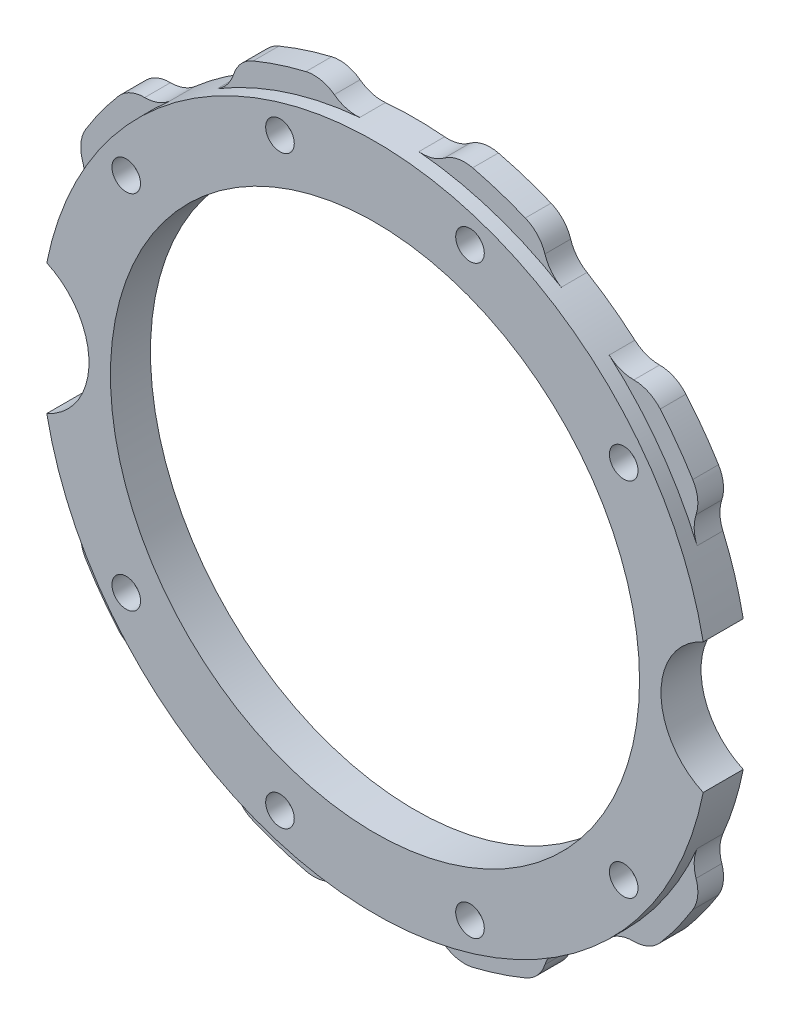
SolidWorks part; units mm, degrees
material "2014 Legierung"
ref_plane "Vorne" through (0, 0, 0) normal (0, 0, 1) x (1, 0, 0)
ref_plane "Oben" through (0, 0, 0) normal (0, 1, 0) x (1, 0, 0)
ref_plane "Rechts" through (0, 0, 0) normal (1, 0, 0) x (0, 0, -1)
sketch "Skizze1" plane through (0, 0, 0) normal (0, 0, 1) x (1, 0, 0)
  line L0 (3.9109, 24.6922) -> (3.6762, 23.2107) construction
  line L1 (0, 0) -> (0, 46.5) construction
  line L2 (-7.2742, 45.9275) -> (0, 0) construction
  line L3 (0, 0) -> (-10.9794, 21.5483) construction
  line L4 (-6.6439, 20.4477) -> (0, 0) construction
  arc A0 (15.4399, 17.7161) -> (17.1008, 17.1008) centre (17.0825, 19.6007) ccw construction
  arc A1 (17.1008, 17.1008) -> (19.0213, 16.2232) centre (17.1191, 14.6009) cw construction
  circle A2 centre (2.299, 25.8982) radius 2.5 construction
  circle A3 centre (5.2675, 21.8747) radius 2.5 construction
  arc A4 (2.0779, 23.408) -> (3.7832, 23.8864) centre (2.299, 25.8982) ccw construction
  arc A5 (3.7832, 23.8864) -> (5.8528, 24.3052) centre (5.2675, 21.8747) cw construction
  arc A6 (-2.0779, 23.408) -> (-3.7832, 23.8864) centre (-2.299, 25.8982) cw construction
  arc A7 (-3.7832, 23.8864) -> (-5.8528, 24.3052) centre (-5.2675, 21.8747) ccw construction
  arc A8 (12.0778, 20.1588) -> (10.9794, 21.5483) centre (13.3626, 22.3034) cw construction
  arc A9 (10.9794, 21.5483) -> (9.5513, 23.1035) centre (8.5962, 20.7932) ccw construction
  arc A10 (15.4399, 17.7161) -> (12.0778, 20.1588) centre (0, 0) ccw construction
  arc A11 (-22.9044, 5.2572) -> (-22.9044, -5.2572) centre (0, 0) ccw construction
  arc A12 (22.9044, 5.2572) -> (22.9044, -5.2572) centre (0, 0) cw construction
  arc A13 (21.6202, 9.2097) -> (21.5483, 10.9794) centre (23.9202, 10.1894) cw construction
  arc A14 (21.5483, 10.9794) -> (21.3071, 13.077) centre (19.1764, 11.7693) ccw construction
  arc A15 (22.9044, 5.2572) -> (21.6202, 9.2097) centre (0, 0) ccw construction
  arc A16 (21.6202, -9.2097) -> (21.5483, -10.9794) centre (23.9202, -10.1894) ccw construction
  arc A17 (21.5483, -10.9794) -> (21.3071, -13.077) centre (19.1764, -11.7693) cw construction
  arc A18 (-22.8069, 5.2348) -> (-22.8069, -5.2348) centre (0, 0) ccw
  arc A19 (-22.8069, -5.2348) -> (-21.5282, -9.1705) centre (0, 0) ccw
  arc A20 (21.6202, -9.2097) -> (22.9044, -5.2572) centre (0, 0) ccw construction
  arc A21 (12.0778, -20.1588) -> (10.9794, -21.5483) centre (13.3626, -22.3034) ccw construction
  arc A22 (10.9794, -21.5483) -> (9.5513, -23.1035) centre (8.5962, -20.7932) cw construction
  arc A23 (15.4399, -17.7161) -> (17.1008, -17.1008) centre (17.0825, -19.6007) cw construction
  arc A24 (17.1008, -17.1008) -> (19.0213, -16.2232) centre (17.1191, -14.6009) ccw construction
  arc A25 (12.0778, -20.1588) -> (15.4399, -17.7161) centre (0, 0) ccw construction
  arc A26 (-2.0779, -23.408) -> (-3.7832, -23.8864) centre (-2.299, -25.8982) ccw construction
  arc A27 (-3.7832, -23.8864) -> (-5.8528, -24.3052) centre (-5.2675, -21.8747) cw construction
  arc A28 (2.0779, -23.408) -> (3.7832, -23.8864) centre (2.299, -25.8982) cw construction
  arc A29 (3.7832, -23.8864) -> (5.8528, -24.3052) centre (5.2675, -21.8747) ccw construction
  arc A30 (-2.0779, -23.408) -> (2.0779, -23.408) centre (0, 0) ccw construction
  arc A31 (-15.4399, -17.7161) -> (-17.1008, -17.1008) centre (-17.0825, -19.6007) ccw construction
  arc A32 (-17.1008, -17.1008) -> (-19.0213, -16.2232) centre (-17.1191, -14.6009) cw construction
  arc A33 (-12.0778, -20.1588) -> (-10.9794, -21.5483) centre (-13.3626, -22.3034) cw construction
  arc A34 (-10.9794, -21.5483) -> (-9.5513, -23.1035) centre (-8.5962, -20.7932) ccw construction
  arc A35 (-15.4399, -17.7161) -> (-12.0778, -20.1588) centre (0, 0) ccw construction
  arc A36 (-21.5282, -9.1705) -> (-21.4534, -11.011) centre (-23.9202, -10.1894) cw
  arc A37 (-21.4534, -11.011) -> (-21.2218, -13.0247) centre (-19.1764, -11.7693) ccw
  arc A38 (-21.6202, -9.2097) -> (-21.5483, -10.9794) centre (-23.9202, -10.1894) cw construction
  arc A39 (-21.5483, -10.9794) -> (-21.3071, -13.077) centre (-19.1764, -11.7693) ccw construction
  arc A40 (-22.9044, -5.2572) -> (-21.6202, -9.2097) centre (0, 0) ccw construction
  arc A41 (-21.6202, 9.2097) -> (-21.5483, 10.9794) centre (-23.9202, 10.1894) ccw construction
  arc A42 (-21.5483, 10.9794) -> (-21.3071, 13.077) centre (-19.1764, 11.7693) cw construction
  arc A43 (-21.2218, -13.0247) -> (-18.9452, -16.1583) centre (0, 0) ccw
  arc A44 (-17.1015, -17.0008) -> (-18.9452, -16.1583) centre (-17.1191, -14.6009) cw
  arc A45 (-21.6202, 9.2097) -> (-22.9044, 5.2572) centre (0, 0) ccw construction
  arc A46 (-12.0778, 20.1588) -> (-10.9794, 21.5483) centre (-13.3626, 22.3034) ccw construction
  arc A47 (-10.9794, 21.5483) -> (-9.5513, 23.1035) centre (-8.5962, 20.7932) cw construction
  arc A48 (-15.4399, 17.7161) -> (-17.1008, 17.1008) centre (-17.0825, 19.6007) cw construction
  arc A49 (-17.1008, 17.1008) -> (-19.0213, 16.2232) centre (-17.1191, 14.6009) ccw construction
  arc A50 (-12.0778, 20.1588) -> (-15.4399, 17.7161) centre (0, 0) ccw construction
  arc A51 (-19.0213, 16.2232) -> (-21.3071, 13.077) centre (0, 0) ccw construction
  arc A52 (-5.8528, 24.3052) -> (-9.5513, 23.1035) centre (0, 0) ccw construction
  arc A53 (-15.3742, -17.6407) -> (-17.1015, -17.0008) centre (-17.0825, -19.6007) ccw
  arc A54 (9.5513, 23.1035) -> (5.8528, 24.3052) centre (0, 0) ccw construction
  arc A55 (21.3071, 13.077) -> (19.0213, 16.2232) centre (0, 0) ccw construction
  arc A56 (-21.3071, -13.077) -> (-19.0213, -16.2232) centre (0, 0) ccw construction
  arc A57 (-9.5513, -23.1035) -> (-5.8528, -24.3052) centre (0, 0) ccw construction
  arc A58 (5.8528, -24.3052) -> (9.5513, -23.1035) centre (0, 0) ccw construction
  arc A59 (19.0213, -16.2232) -> (21.3071, -13.077) centre (0, 0) ccw construction
  arc A60 (-15.3742, -17.6407) -> (-12.0264, -20.073) centre (0, 0) ccw
  arc A61 (-12.0264, -20.073) -> (-10.8841, -21.5181) centre (-13.3626, -22.3034) cw
  arc A62 (-10.8841, -21.5181) -> (-9.5131, -23.0111) centre (-8.5962, -20.7932) ccw
  arc A63 (-9.5131, -23.0111) -> (-5.8294, -24.208) centre (0, 0) ccw
  arc A64 (-3.8426, -23.806) -> (-5.8294, -24.208) centre (-5.2675, -21.8747) cw
  arc A65 (-2.0691, -23.3083) -> (-3.8426, -23.806) centre (-2.299, -25.8982) ccw
  arc A66 (-2.0691, -23.3083) -> (2.0691, -23.3083) centre (0, 0) ccw
  arc A67 (2.0691, -23.3083) -> (3.8426, -23.806) centre (2.299, -25.8982) cw
  arc A68 (3.8426, -23.806) -> (5.8294, -24.208) centre (5.2675, -21.8747) ccw
  arc A69 (5.8294, -24.208) -> (9.5131, -23.0111) centre (0, 0) ccw
  arc A70 (10.8841, -21.5181) -> (9.5131, -23.0111) centre (8.5962, -20.7932) cw
  arc A71 (12.0264, -20.073) -> (10.8841, -21.5181) centre (13.3626, -22.3034) ccw
  arc A72 (12.0264, -20.073) -> (15.3742, -17.6407) centre (0, 0) ccw
  arc A73 (15.3742, -17.6407) -> (17.1015, -17.0008) centre (17.0825, -19.6007) cw
  arc A74 (17.1015, -17.0008) -> (18.9452, -16.1583) centre (17.1191, -14.6009) ccw
  arc A75 (18.9452, -16.1583) -> (21.2218, -13.0247) centre (0, 0) ccw
  arc A76 (2.0779, 23.408) -> (-2.0779, 23.408) centre (0, 0) ccw construction
  arc A77 (21.4534, -11.011) -> (21.2218, -13.0247) centre (19.1764, -11.7693) cw
  arc A78 (21.5282, -9.1705) -> (21.4534, -11.011) centre (23.9202, -10.1894) ccw
  arc A79 (21.5282, -9.1705) -> (22.8069, -5.2348) centre (0, 0) ccw
  arc A80 (22.8069, 5.2348) -> (22.8069, -5.2348) centre (0, 0) cw
  arc A81 (22.8069, 5.2348) -> (21.5282, 9.1705) centre (0, 0) ccw
  arc A82 (21.5282, 9.1705) -> (21.4534, 11.011) centre (23.9202, 10.1894) cw
  arc A83 (21.4534, 11.011) -> (21.2218, 13.0247) centre (19.1764, 11.7693) ccw
  arc A84 (21.2218, 13.0247) -> (18.9452, 16.1583) centre (0, 0) ccw
  arc A85 (17.1015, 17.0008) -> (18.9452, 16.1583) centre (17.1191, 14.6009) cw
  arc A86 (15.3742, 17.6407) -> (17.1015, 17.0008) centre (17.0825, 19.6007) ccw
  arc A87 (15.3742, 17.6407) -> (12.0264, 20.073) centre (0, 0) ccw
  arc A88 (12.0264, 20.073) -> (10.8841, 21.5181) centre (13.3626, 22.3034) cw
  arc A89 (10.8841, 21.5181) -> (9.5131, 23.0111) centre (8.5962, 20.7932) ccw
  arc A90 (9.5131, 23.0111) -> (5.8294, 24.208) centre (0, 0) ccw
  arc A91 (3.8426, 23.806) -> (5.8294, 24.208) centre (5.2675, 21.8747) cw
  arc A92 (2.0691, 23.3083) -> (3.8426, 23.806) centre (2.299, 25.8982) ccw
  arc A93 (2.0691, 23.3083) -> (-2.0691, 23.3083) centre (0, 0) ccw
  arc A94 (-2.0691, 23.3083) -> (-3.8426, 23.806) centre (-2.299, 25.8982) cw
  arc A95 (-3.8426, 23.806) -> (-5.8294, 24.208) centre (-5.2675, 21.8747) ccw
  arc A96 (-5.8294, 24.208) -> (-9.5131, 23.0111) centre (0, 0) ccw
  arc A97 (-10.8841, 21.5181) -> (-9.5131, 23.0111) centre (-8.5962, 20.7932) cw
  arc A98 (-12.0264, 20.073) -> (-10.8841, 21.5181) centre (-13.3626, 22.3034) ccw
  arc A99 (-12.0264, 20.073) -> (-15.3742, 17.6407) centre (0, 0) ccw
  arc A100 (-15.3742, 17.6407) -> (-17.1015, 17.0008) centre (-17.0825, 19.6007) cw
  arc A101 (-17.1015, 17.0008) -> (-18.9452, 16.1583) centre (-17.1191, 14.6009) ccw
  arc A102 (-18.9452, 16.1583) -> (-21.2218, 13.0247) centre (0, 0) ccw
  arc A103 (-21.4534, 11.011) -> (-21.2218, 13.0247) centre (-19.1764, 11.7693) cw
  arc A104 (-21.5282, 9.1705) -> (-21.4534, 11.011) centre (-23.9202, 10.1894) ccw
  arc A105 (-21.5282, 9.1705) -> (-22.8069, 5.2348) centre (0, 0) ccw
  circle A106 centre (0, 0) radius 18.5
  circle A107 centre (-6.6439, 20.4477) radius 1 construction
  circle A108 centre (-6.6439, 20.4477) radius 2 construction
  circle A110 centre (0, 0) radius 23.5 construction
  arc A113 (-22.9044, -5.2572) -> (-23.8864, -3.7832) centre (-25.341, -5.8165) ccw [skipped]
  arc A114 (-23.8864, -3.7832) -> (-24.9243, -1.9444) centre (-22.4318, -1.75) cw [skipped]
  arc A115 (-22.9044, 5.2572) -> (-23.8864, 3.7832) centre (-25.341, 5.8165) cw [skipped]
  arc A116 (-23.8864, 3.7832) -> (-24.9243, 1.9444) centre (-22.4318, 1.75) ccw [skipped]
  arc A117 (22.9044, 5.2572) -> (23.8864, 3.7832) centre (25.341, 5.8165) ccw [skipped]
  arc A118 (23.8864, 3.7832) -> (24.9243, 1.9444) centre (22.4318, 1.75) cw [skipped]
  arc A119 (22.9044, -5.2572) -> (23.8864, -3.7832) centre (25.341, -5.8165) cw [skipped]
  arc A120 (23.8864, -3.7832) -> (24.9243, -1.9444) centre (22.4318, -1.75) ccw [skipped]
  point P3 (-23.8864, -3.7832)
  point P13 (3.7832, 23.8864)
  point P24 (23.8864, 3.7832)
  point P27 (17.1008, 17.1008)
  point P51 (21.5483, -10.9794)
  point P63 (10.9794, -21.5483)
  point P75 (-3.7832, -23.8864)
  point P87 (-17.1008, -17.1008)
  point P111 (-21.5483, 10.9794)
  point P123 (-10.9794, 21.5483)
  dimension "D1" = 25
  dimension "D2" = 23.5
  dimension "D4" = 5
  dimension "D5" = 0.1
  dimension "D7" = 4
  dimension "D8" = 2
  dimension "D9" = 37
  dimension "D3" = 18
  dimension "D6" = 18
  dimension "D10" = 18
  dimension "D11" = 21.5
extrude "Linear austragen1" add sketch "Skizze1" along normal blind 1.8
sketch "Skizze2" plane through (0, 0, 1.8) normal (0, 0, 1) x (1, 0, 0)
  circle A0 centre (0, 0) radius 18.5
  circle A1 centre (0, 0) radius 23.4
  arc A2 (2.0691, 23.3083) -> (-2.0691, 23.3083) centre (0, 0) ccw construction
  circle A3 centre (0, 0) radius 18.5 construction
extrude "Linear austragen2" add sketch "Skizze2" along normal blind 1
sketch "Skizze3" plane through (0, 0, 2.8) normal (0, 0, 1) x (1, 0, 0)
  circle A0 centre (-6.6439, 20.4477) radius 1
  circle A1 centre (-6.6439, 20.4477) radius 1 construction
  circle A2 centre (6.6439, 20.4477) radius 1
  circle A3 centre (17.3939, 12.6374) radius 1
  circle A5 centre (17.3939, -12.6374) radius 1
  circle A6 centre (6.6439, -20.4477) radius 1
  circle A7 centre (-6.6439, -20.4477) radius 1
  circle A8 centre (-17.3939, -12.6374) radius 1
  circle A10 centre (-17.3939, 12.6374) radius 1
  circle A11 centre (21.5, 0) radius 1 [skipped]
  circle A12 centre (-21.5, 0) radius 1 [skipped]
  dimension "D1" = 10
extrude "Schnitt-Linear austragen1" cut sketch "Skizze3" against normal through all
chamfer "Chamfer1" distance 1.4 angle 45 8 edges at (18.3939, 12.6374, 0) (7.6439, 20.4477, 0) (-5.6439, 20.4477, 0) (-16.3939, 12.6374, 0) (-16.3939, -12.6374, 0) (18.3939, -12.6374, 0) (7.6439, -20.4477, 0) (-5.6439, -20.4477, 0)
sketch "Sketch1" plane through (0, 0, 0) normal (0, 0, -1) x (-1, 0, 0)
  line L0 (-28.4164, 0) -> (28.4164, 0) construction
  circle A0 centre (-25, 0) radius 5
  circle A1 centre (25, 0) radius 5
  dimension "D3" = 10
  dimension "D4" = 10
  dimension "D1" = 25
  dimension "D2" = 25
extrude "Cut-Extrude1" cut sketch "Sketch1" against normal blind 10
